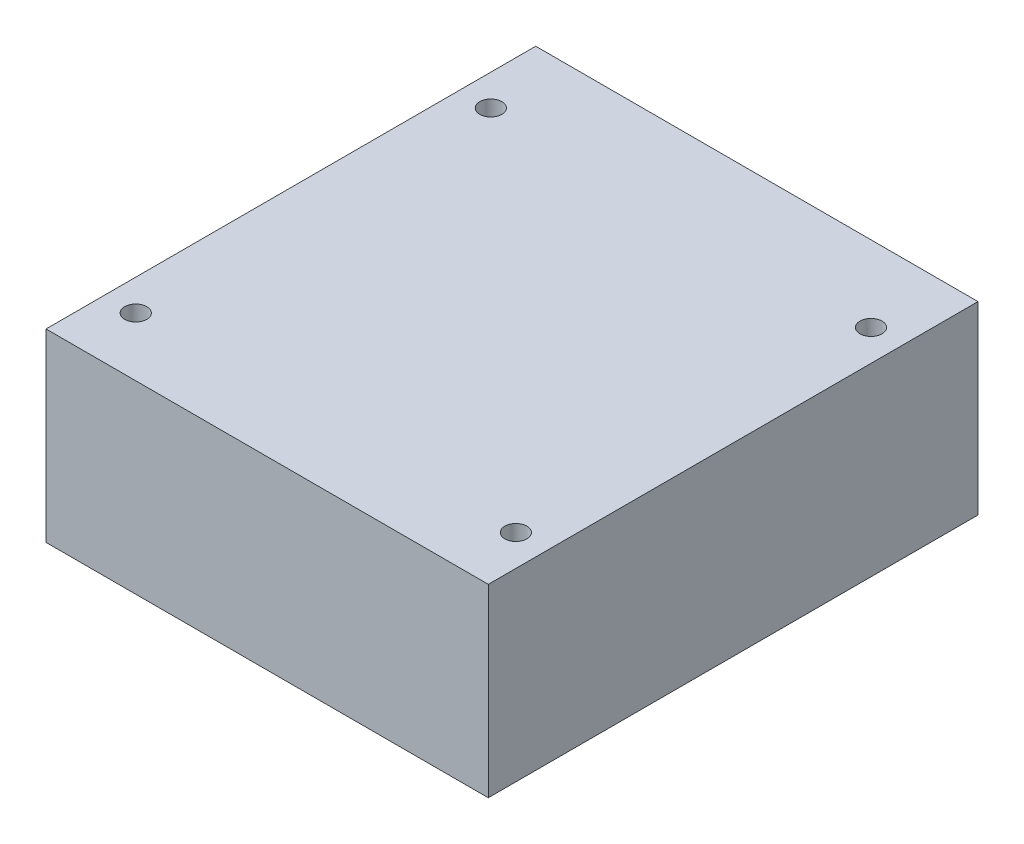
SolidWorks part; units mm, degrees
ref_plane "Front Plane" through (0, 0, 0) normal (0, 0, 1) x (1, 0, 0)
ref_plane "Top Plane" through (0, 0, 0) normal (0, 1, 0) x (1, 0, 0)
ref_plane "Right Plane" through (0, 0, 0) normal (1, 0, 0) x (0, 0, -1)
sketch "Sketch1" plane through (0, 0, 0) normal (0, 1, 0) x (1, 0, 0)
  line L1 (-32.035, 35.47) -> (32.035, 35.47)
  line L2 (-32.035, 35.47) -> (-32.035, -35.47)
  line L3 (-32.035, -35.47) -> (32.035, -35.47)
  line L4 (32.035, 35.47) -> (32.035, -35.47)
  line L5 (-32.035, 35.47) -> (32.035, -35.47) construction
  line L6 (-32.035, -35.47) -> (32.035, 35.47) construction
  point P0 (0, 0)
  dimension "D1" = 70.94
  dimension "D2" = 64.07
extrude "Boss-Extrude1" add sketch "Sketch1" along normal blind 26.78
sketch "Sketch4" plane through (0, 26.78, 0) normal (0, 1, 0) x (1, 0, 0)
  line L0 (-32.035, 35.47) -> (-32.035, -35.47) construction
  line L1 (32.035, 35.47) -> (-32.035, 35.47) construction
  line L2 (0, 0) -> (0, 22.2452) construction
  line L3 (-32.035, -35.47) -> (32.035, -35.47) construction
  circle A0 centre (-27.535, 24.47) radius 1.6
  circle A1 centre (27.535, 24.47) radius 1.6
  circle A2 centre (-27.535, -26.97) radius 1.6
  circle A3 centre (27.535, -26.97) radius 1.6
  dimension "D1" = 4.5
  dimension "D3" = 4.5
  dimension "D5" = 3.2
  dimension "D6" = 3.2
  dimension "D2" = 11
  dimension "D4" = 8.5
extrude "Cut-Extrude1" cut sketch "Sketch4" against normal through all
